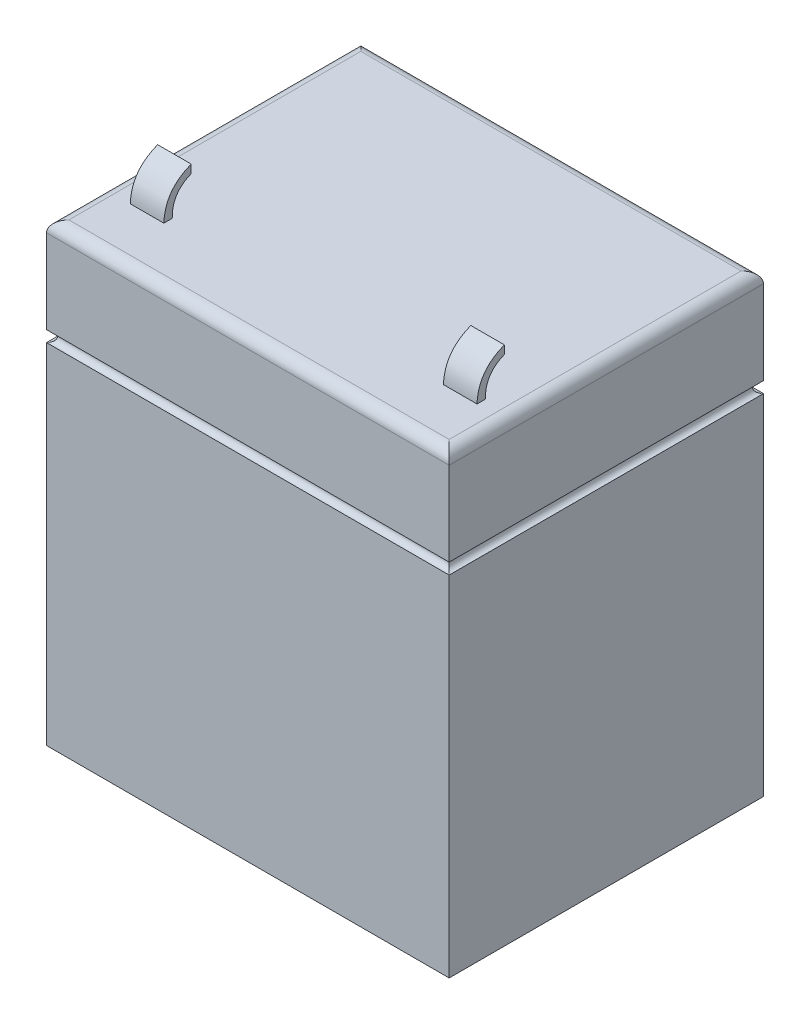
SolidWorks part; units mm, degrees
ref_plane "Front Plane" through (0, 0, 0) normal (0, 0, 1) x (1, 0, 0)
ref_plane "Top Plane" through (0, 0, 0) normal (0, 1, 0) x (1, 0, 0)
ref_plane "Right Plane" through (0, 0, 0) normal (1, 0, 0) x (0, 0, -1)
sketch "Sketch1" plane through (0, 0, 0) normal (0, 1, 0) x (1, 0, 0)
  line L1 (0, 0) -> (91.44, 0)
  line L2 (0, 0) -> (0, 71.374)
  line L3 (0, 71.374) -> (91.44, 71.374)
  line L4 (91.44, 0) -> (91.44, 71.374)
  dimension "D1" = 91.44
  dimension "D2" = 71.374
extrude "Boss-Extrude1" add sketch "Sketch1" along normal blind 103.378
sketch "Sketch2" plane through (91.44, 0, 0) normal (1, 0, 0) x (0, 0, -1)
  line L0 (12.671, 103.378) -> (14.576, 103.378)
  line L1 (0, 103.378) -> (71.374, 103.378) construction
  line L2 (18.8822, 109.9988) -> (18.8822, 111.9038)
  spline S0 degree 2 poles (12.671, 103.378) (12.9199, 109.6023) (18.8822, 111.9038) knots 0 0 0 1 1 1
  spline S1 degree 2 poles (14.576, 103.378) (14.4616, 108.2558) (18.8822, 109.9988) knots 0 0 0 1 1 1
  point P9 (0, 0)
  dimension "D1" = 1.905
  dimension "D2" = 1.905
extrude "Boss-Extrude2" add sketch "Sketch2" against normal blind 91.44
sketch "Sketch3" plane through (0, 0, 0) normal (0, 0, 1) x (1, 0, 0)
  line L0 (0, 111.9038) -> (91.44, 111.9038) construction
  line L1 (0, 103.378) -> (6.35, 103.378)
  line L2 (0, 103.378) -> (0, 111.9038)
  line L3 (0, 111.9038) -> (6.35, 111.9038)
  line L4 (6.35, 103.378) -> (6.35, 111.9038)
  line L5 (0, 103.378) -> (91.44, 103.378) construction
  line L6 (13.97, 103.378) -> (77.47, 103.378)
  line L7 (13.97, 103.378) -> (13.97, 111.9038)
  line L8 (13.97, 111.9038) -> (77.47, 111.9038)
  line L9 (77.47, 103.378) -> (77.47, 111.9038)
  line L10 (45.72, 0) -> (45.72, 111.9038) construction
  line L11 (91.44, 103.378) -> (85.09, 103.378)
  line L12 (91.44, 103.378) -> (91.44, 111.9038)
  line L13 (91.44, 111.9038) -> (85.09, 111.9038)
  line L14 (85.09, 103.378) -> (85.09, 111.9038)
  line L15 (0, 0) -> (91.44, 0) construction
  point P22 (45.72, 103.378)
  dimension "D1" = 6.35
  dimension "D2" = 63.5
extrude "Cut-Extrude1" cut sketch "Sketch3" against normal through all
fillet "Fillet1" radius 2.54 4 edges at (0, 103.378, -35.687) (45.72, 103.378, 0) (45.72, 103.378, -71.374) (91.44, 103.378, -35.687)
sketch "Sketch4" plane through (0, 0, 0) normal (-1, 0, 0) x (0, 0, 1)
  line L0 (-71.374, 100.838) -> (-71.374, 0) construction
  line L1 (0, 100.838) -> (0, 0) construction
  line L2 (-71.374, 80.518) -> (0, 80.518) construction
  line L3 (-68.834, 103.378) -> (-2.54, 103.378) construction
  circle A0 centre (-71.374, 80.518) radius 1.27
  circle A1 centre (0, 80.518) radius 1.27
  point P6 (0, 0)
  dimension "D1" = 2.54
  dimension "D2" = 22.86
extrude "Cut-Extrude2" cut sketch "Sketch4" against normal through all and the other way through all
sketch "Sketch5" plane through (0, 0, 0) normal (0, 0, 1) x (1, 0, 0)
  line L0 (0, 81.788) -> (0, 79.248) construction
  line L1 (91.44, 79.248) -> (91.44, 81.788) construction
  circle A0 centre (0, 80.518) radius 1.27
  circle A1 centre (91.44, 80.518) radius 1.27
extrude "Cut-Extrude3" cut sketch "Sketch5" against normal through all
